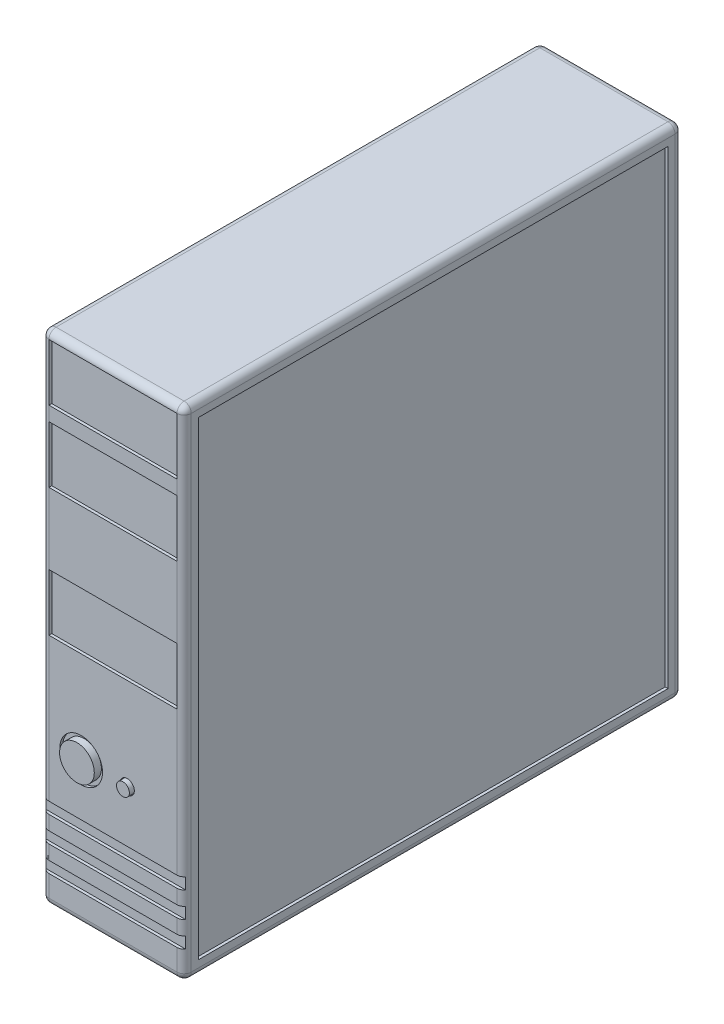
SolidWorks part; units mm, degrees
ref_plane "Alzado" through (0, 0, 0) normal (0, 0, 1) x (1, 0, 0)
ref_plane "Planta" through (0, 0, 0) normal (0, 1, 0) x (1, 0, 0)
ref_plane "Vista lateral" through (0, 0, 0) normal (1, 0, 0) x (0, 0, -1)
sketch "Croquis1" plane through (0, 0, 0) normal (0, 0, 1) x (1, 0, 0)
  line L0 (50, 175) -> (-50, -175) construction
  line L1 (-50, 175) -> (50, 175)
  line L2 (-50, 175) -> (-50, -175)
  line L3 (-50, -175) -> (50, -175)
  line L4 (50, 175) -> (50, -175)
  dimension "D1" = 100
  dimension "D2" = 350
extrude "Saliente-Extruir1" add sketch "Croquis1" against normal blind 350
fillet "Redondeo1" radius 5 12 edges at (-50, 175, -175) (50, 175, -175) (50, -175, -175) (-50, -175, -175) (0, 175, -350) (50, 0, -350) (0, -175, -350) (-50, 0, -350) (0, 175, 0) (50, 0, 0) (0, -175, 0) (-50, 0, 0)
sketch "Croquis2" plane through (0, 0, 0) normal (0, 0, 1) x (1, 0, 0)
  line L0 (45, -170) -> (45, 170) construction
  line L1 (-45, 170) -> (45, 170)
  line L2 (-45, 170) -> (-45, 130)
  line L3 (-45, 130) -> (45, 130)
  line L4 (45, 170) -> (45, 130)
  line L5 (-45, 170) -> (-45, -170) construction
  line L6 (-45, 120) -> (45, 120)
  line L7 (-45, 120) -> (-45, 80)
  line L8 (-45, 80) -> (45, 80)
  line L9 (45, 120) -> (45, 80)
  line L10 (-45, -170) -> (45, -170) construction
  line L11 (-45, 30) -> (45, 30)
  line L12 (-45, 30) -> (-45, -10)
  line L13 (-45, -10) -> (45, -10)
  line L14 (45, 30) -> (45, -10)
  line L15 (-53.2227, -147) -> (52.2922, -147)
  line L16 (-53.2227, -147) -> (-53.2227, -155)
  line L17 (-53.2227, -155) -> (52.2922, -155)
  line L18 (52.2922, -147) -> (52.2922, -155)
  line L19 (-53.2227, -129) -> (52.2922, -129)
  line L20 (-53.2227, -129) -> (-53.2227, -137)
  line L21 (-53.2227, -137) -> (52.2922, -137)
  line L22 (52.2922, -129) -> (52.2922, -137)
  line L23 (-53.2227, -111) -> (52.2922, -111)
  line L24 (-53.2227, -111) -> (-53.2227, -119)
  line L25 (-53.2227, -119) -> (52.2922, -119)
  line L26 (52.2922, -111) -> (52.2922, -119)
  line L27 (-45, -74.6899) -> (45, -74.6899) construction
  circle A0 centre (-22.3398, -74.6899) radius 15
  circle A1 centre (10.0149, -74.6899) radius 5
  dimension "D12" = 30
  dimension "D13" = 10
  dimension "D1" = 10
  dimension "D2" = 10
  dimension "D3" = 15
  dimension "D4" = 8
  dimension "D5" = 8
  dimension "D6" = 8
  dimension "D7" = 40
  dimension "D8" = 10
  dimension "D9" = 40
  dimension "D10" = 50
  dimension "D11" = 40
extrude "Cortar-Extruir1" cut sketch "Croquis2" against normal blind 2
sketch "Croquis3" plane through (0, 0, -2) normal (0, 0, 1) x (1, 0, 0)
  circle A0 centre (-22.3398, -74.6899) radius 12.2037
  circle A1 centre (10.0149, -74.6899) radius 4.5213
extrude "Saliente-Extruir2" add sketch "Croquis3" along normal blind 5
sketch "Croquis4" plane through (-50, 0, 0) normal (-1, 0, 0) x (0, 0, 1)
  line L0 (-5, 170) -> (-345, 170) construction
  line L1 (-340, 165) -> (-10, 165)
  line L2 (-340, 165) -> (-340, -165)
  line L3 (-340, -165) -> (-10, -165)
  line L4 (-10, 165) -> (-10, -165)
  line L5 (-345, 170) -> (-345, -170) construction
  line L6 (-5, -170) -> (-5, 170) construction
  line L7 (-345, -170) -> (-5, -170) construction
  dimension "D1" = 5
  dimension "D2" = 5
  dimension "D3" = 5
  dimension "D4" = 5
extrude "Cortar-Extruir2" cut sketch "Croquis4" against normal blind 72
sketch "Croquis5" plane through (50, 0, 0) normal (1, 0, 0) x (0, 0, -1)
  line L0 (345, 170) -> (5, 170) construction
  line L1 (10, 165) -> (340, 165)
  line L2 (10, 165) -> (10, -165)
  line L3 (10, -165) -> (340, -165)
  line L4 (340, 165) -> (340, -165)
  line L5 (345, -170) -> (345, 170) construction
  line L6 (5, -170) -> (345, -170) construction
  line L7 (5, 170) -> (5, -170) construction
  dimension "D1" = 5
  dimension "D2" = 5
  dimension "D3" = 5
  dimension "D4" = 5
extrude "Cortar-Extruir3" cut sketch "Croquis5" against normal blind 2
